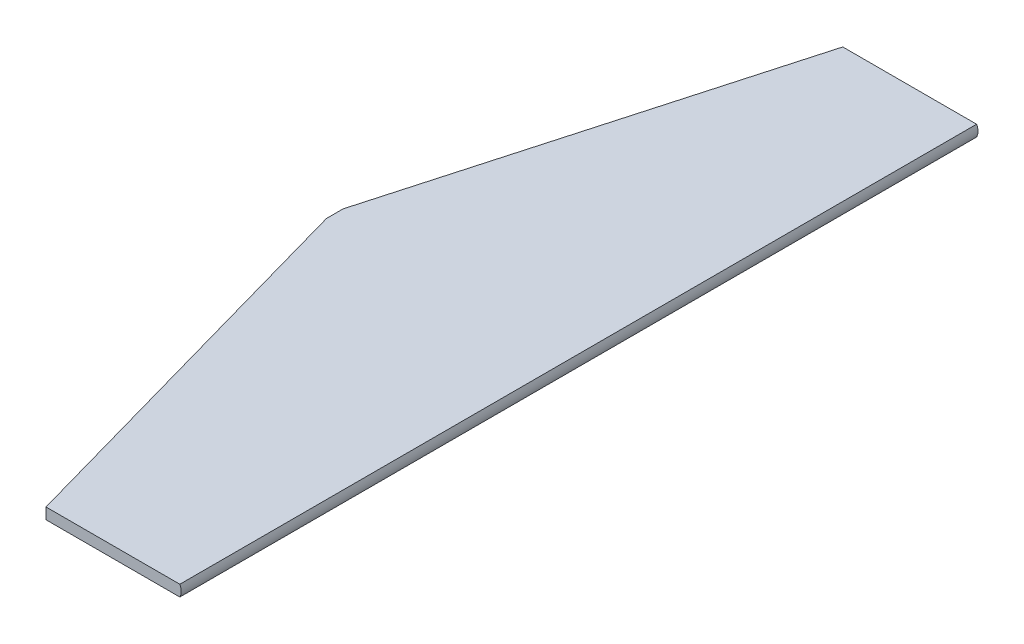
SolidWorks part; units mm, degrees
ref_plane "Front Plane" through (0, 0, 0) normal (0, 0, 1) x (1, 0, 0)
ref_plane "Top Plane" through (0, 0, 0) normal (0, 1, 0) x (1, 0, 0)
ref_plane "Right Plane" through (0, 0, 0) normal (1, 0, 0) x (0, 0, -1)
sketch "Sketch1" plane through (0, 0, 0) normal (0, 1, 0) x (1, 0, 0)
  line L1 (219, 0) -> (219, 350.9)
  line L2 (219, 350.9) -> (98.6, 350.9)
  line L3 (98.6, 350.9) -> (0, 0)
  line L4 (-18.1002, -7.5) -> (0, -7.5) construction
  line L5 (219, -365.9) -> (98.6, -365.9)
  line L6 (219, -15) -> (219, -365.9)
  line L8 (98.6, -365.9) -> (0, -15)
  line L9 (0, 0) -> (0, -15)
  line L10 (219, 0) -> (219, -15)
  line L11 (219, -7.5) -> (272.9736, -7.5) construction
  dimension "D1" = 219
  dimension "D2" = 350.9
  dimension "D3" = 120.4
extrude "Boss-Extrude1" add sketch "Sketch1" along normal blind 10
scale "Scale2" scale about centroid uniform scaling yes scale factor 0.6
sketch "Sketch2" plane through (0, 0, 222.54) normal (0, 0, 1) x (1, 0, 0)
  line L0 (183.8661, 8) -> (183.8661, 2)
  arc A0 (183.8661, 8) -> (183.8661, 2) centre (178.2537, 5) cw
extrude "Boss-Extrude2" add sketch "Sketch2" against normal up to surface (430.08 mm away) up to face at (147.7461, 5, -207.54)
